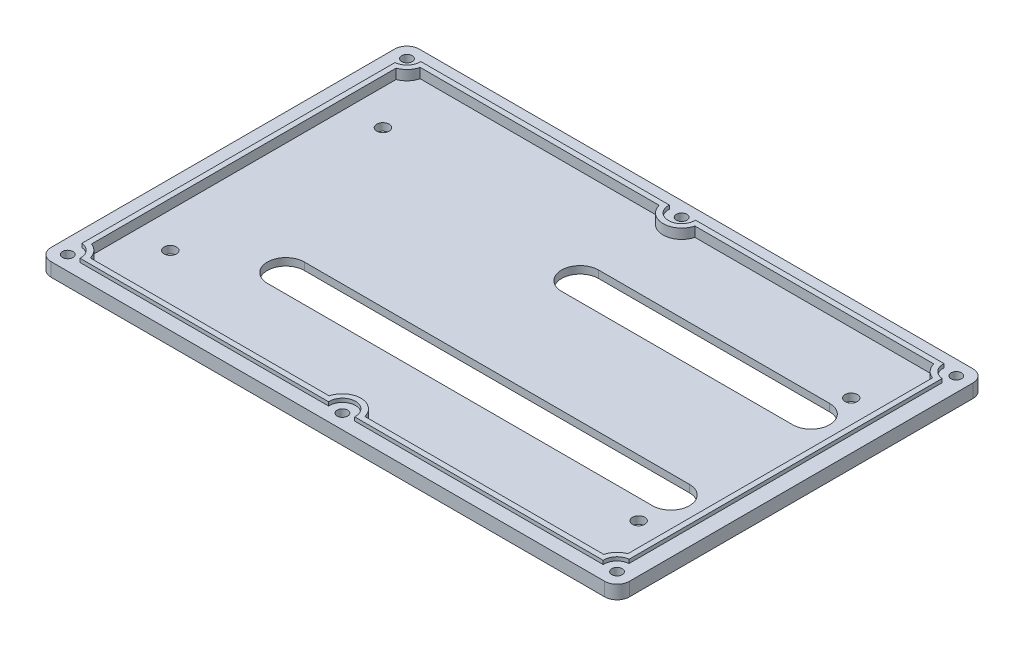
SolidWorks part; units mm, degrees
ref_plane "Front Plane" through (0, 0, 0) normal (0, 0, 1) x (1, 0, 0)
ref_plane "Top Plane" through (0, 0, 0) normal (0, 1, 0) x (1, 0, 0)
ref_plane "Right Plane" through (0, 0, 0) normal (1, 0, 0) x (0, 0, -1)
sketch "Sketch1" plane through (0, 0, 0) normal (0, 1, 0) x (1, 0, 0)
  line L0 (0, 0) -> (0, -54.75) construction
  line L1 (-89.85, 59.75) -> (89.85, 59.75)
  line L2 (-93.85, 55.75) -> (-93.85, -55.75)
  line L3 (-89.85, -59.75) -> (89.85, -59.75)
  line L4 (93.85, 55.75) -> (93.85, -55.75)
  line L5 (-93.85, 59.75) -> (93.85, -59.75) construction
  line L6 (-93.85, -59.75) -> (93.85, 59.75) construction
  line L7 (0, -54.75) -> (88.9, -54.75) construction
  line L8 (88.9, -54.75) -> (88.9, 0.25) construction
  line L9 (88.9, 0.25) -> (71.9, 0.25) construction
  line L10 (71.9, 0.25) -> (53.9, 0.25) construction
  line L11 (0, 0) -> (0, 54.75) construction
  line L12 (0, 54.75) -> (-88.9, 54.75) construction
  line L13 (-88.9, 54.75) -> (-68.9, 54.75) construction
  line L14 (-68.9, 54.75) -> (-68.9, 19.75) construction
  line L15 (-68.9, 19.75) -> (-68.9, -15.25) construction
  arc A0 (-93.85, -55.75) -> (-89.85, -59.75) centre (-89.85, -55.75) ccw
  arc A1 (89.85, -59.75) -> (93.85, -55.75) centre (89.85, -55.75) ccw
  arc A2 (93.85, 55.75) -> (89.85, 59.75) centre (89.85, 55.75) ccw
  arc A3 (-89.85, 59.75) -> (-93.85, 55.75) centre (-89.85, 55.75) ccw
  point P0 (0, 0)
  dimension "D3" = 4
  dimension "D1" = 119.5
  dimension "D2" = 187.7
  dimension "D4" = 17
  dimension "D5" = 35
  dimension "D6" = 55
  dimension "D7" = 88.9
  dimension "D8" = 54.75
  dimension "D9" = 20
  dimension "D10" = 35
  dimension "D11" = 70
extrude "Boss-Extrude1" add sketch "Sketch1" along normal blind 4.4
sketch "Sketch2" plane through (0, 4.4, 0) normal (0, 1, 0) x (1, 0, 0)
  line L0 (89.85, 59.75) -> (-89.85, 59.75) construction
  line L1 (-87.05, 53.55) -> (87.05, 53.55) construction
  line L2 (-87.05, 53.55) -> (-87.05, -53.55) construction
  line L3 (-87.05, -53.55) -> (87.05, -53.55) construction
  line L4 (87.05, 53.55) -> (87.05, -53.55) construction
  line L5 (-87.05, 53.55) -> (87.05, -53.55) construction
  line L6 (-87.05, -53.55) -> (87.05, 53.55) construction
  line L7 (93.85, -55.75) -> (93.85, 55.75) construction
  line L8 (-93.85, 59.75) -> (-89.15, 59.75) construction
  line L9 (-89.15, 59.75) -> (-89.15, 55.05) construction
  line L10 (93.85, 59.75) -> (89.15, 59.75) construction
  line L11 (89.15, 59.75) -> (89.15, 55.05) construction
  line L12 (93.85, -59.75) -> (89.15, -59.75) construction
  line L13 (-89.85, -59.75) -> (89.85, -59.75) construction
  line L14 (89.15, -59.75) -> (89.15, -55.05) construction
  line L15 (-93.85, -59.75) -> (-89.15, -59.75) construction
  line L16 (-89.15, -59.75) -> (-89.15, -55.05) construction
  line L17 (-83.3405, -53.55) -> (-5.8095, -53.55)
  line L18 (87.05, -49.4295) -> (87.05, 49.4295)
  line L19 (5.8095, -53.55) -> (83.3405, -53.55)
  line L20 (-87.05, 49.4295) -> (-87.05, -49.4295)
  line L21 (-89.15, -55.05) -> (89.15, -55.05) construction
  line L22 (-89.15, 55.05) -> (89.15, 55.05) construction
  line L23 (5.8095, 53.55) -> (83.3405, 53.55)
  line L24 (-5.8095, 53.55) -> (-83.3405, 53.55)
  line L25 (89.85, 59.75) -> (-89.85, 59.75) construction
  line L29 (93.85, -55.75) -> (93.85, 55.75) construction
  line L30 (-89.85, -59.75) -> (89.85, -59.75) construction
  line L31 (-93.85, 55.75) -> (-93.85, -55.75) construction
  arc A0 (83.3405, 53.55) -> (87.05, 49.4295) centre (89.15, 55.05) ccw
  arc A1 (-83.3405, 53.55) -> (-87.05, 49.4295) centre (-89.15, 55.05) cw
  arc A2 (-83.3405, -53.55) -> (-87.05, -49.4295) centre (-89.15, -55.05) ccw
  arc A3 (83.3405, -53.55) -> (87.05, -49.4295) centre (89.15, -55.05) cw
  arc A4 (-5.8095, 53.55) -> (5.8095, 53.55) centre (0, 55.05) ccw
  arc A5 (-5.8095, -53.55) -> (5.8095, -53.55) centre (0, -55.05) cw
  point P0 (0, 0)
  point P36 (0, 55.05)
  point P37 (0, -55.05)
  dimension "D4" = 6
  dimension "D1" = 6.2
  dimension "D2" = 6.8
  dimension "D3" = 4.7
extrude "Cut-Extrude1" cut sketch "Sketch2" against normal blind 2
sketch "Sketch3" plane through (0, 4.4, 0) normal (0, 1, 0) x (1, 0, 0)
  line L0 (-87.05, 49.4295) -> (-87.05, -49.4295)
  line L1 (5.8095, -53.55) -> (83.3405, -53.55)
  line L2 (-5.8095, -53.55) -> (-83.3405, -53.55)
  line L3 (87.05, 49.4295) -> (87.05, -49.4295)
  line L4 (5.8095, -53.55) -> (83.3405, -53.55) construction
  line L5 (-88.8, 50.8144) -> (-88.8, -50.8144)
  line L6 (-4.2426, -55.3) -> (-84.9074, -55.3)
  line L7 (4.2426, -55.3) -> (84.9074, -55.3)
  line L8 (88.8, 50.8144) -> (88.8, -50.8144)
  line L9 (-83.3405, 53.55) -> (-5.8095, 53.55)
  line L10 (4.2426, 55.3) -> (84.9074, 55.3)
  line L11 (-84.9074, 55.3) -> (-4.2426, 55.3)
  line L12 (5.8095, 53.55) -> (83.3405, 53.55)
  arc A0 (-87.05, 49.4295) -> (-83.3405, 53.55) centre (-89.15, 55.05) ccw
  arc A1 (-87.05, 49.4295) -> (-83.3405, 53.55) centre (-89.15, 55.05) ccw construction
  arc A2 (87.05, 49.4295) -> (83.3405, 53.55) centre (89.15, 55.05) cw
  arc A3 (83.3405, 53.55) -> (87.05, 49.4295) centre (89.15, 55.05) ccw construction
  arc A4 (-83.3405, -53.55) -> (-87.05, -49.4295) centre (-89.15, -55.05) ccw
  arc A5 (-83.3405, -53.55) -> (-87.05, -49.4295) centre (-89.15, -55.05) ccw construction
  arc A6 (83.3405, -53.55) -> (87.05, -49.4295) centre (89.15, -55.05) cw
  arc A7 (-84.9074, -55.3) -> (-88.8, -50.8144) centre (-89.15, -55.05) ccw
  arc A8 (87.05, -49.4295) -> (83.3405, -53.55) centre (89.15, -55.05) ccw construction
  arc A9 (-4.2426, -55.3) -> (4.2426, -55.3) centre (0, -55.05) cw
  arc A10 (84.9074, -55.3) -> (88.8, -50.8144) centre (89.15, -55.05) cw
  arc A11 (88.8, 50.8144) -> (84.9074, 55.3) centre (89.15, 55.05) cw
  arc A12 (-4.2426, 55.3) -> (4.2426, 55.3) centre (0, 55.05) ccw
  arc A13 (-5.8095, 53.55) -> (5.8095, 53.55) centre (0, 55.05) ccw
  arc A14 (-5.8095, 53.55) -> (5.8095, 53.55) centre (0, 55.05) ccw construction
  arc A15 (-5.8095, -53.55) -> (5.8095, -53.55) centre (0, -55.05) cw
  arc A16 (5.8095, -53.55) -> (-5.8095, -53.55) centre (0, -55.05) ccw construction
  arc A17 (-88.8, 50.8144) -> (-84.9074, 55.3) centre (-89.15, 55.05) ccw
  dimension "D1" = 1.75
extrude "Boss-Extrude3" add sketch "Sketch3" along normal blind 1.2
hole_wizard "CSK for M3 SFHCS1" positions "Sketch5" profile "Sketch4" countersink size "M3" standard "ANSI Metric" end condition through all
sketch "Sketch5" plane through (-54.9521, 0, 58.5759) normal (0, 1, 0) x (1, 0, 0)
  point P0 (-34.1979, 113.6259)
  point P3 (-34.1979, 3.5259)
  point P6 (144.1021, 3.5259)
  point P9 (144.1021, 113.6259)
  point P13 (54.9521, 3.5259)
  point P16 (54.9521, 113.6259)
sketch "Sketch4" plane through (-89.15, 0, -55.05) normal (1, 0, 0) x (0, 0, -1)
  line L0 (0, 0) -> (0, 5.6)
  line L1 (0, 5.6) -> (1.7, 5.6)
  line L2 (1.7, 5.6) -> (1.7, 1.66)
  line L3 (1.7, 1.66) -> (3.36, 0)
  line L5 (3.36, 0) -> (0, 0)
  line L6 (-1.7, 1.66) -> (-3.36, 0) construction
  line L11 (0, -6.35) -> (0, 107.95) construction
  dimension "Thru Hole Dia." = 3.4
  dimension "Thru Hole Depth" = 5.6
  dimension "Near C'Sink Dia." = 6.72
  dimension "Near C'Sink Angle" = 90
hole_wizard "CSK for M3 SFHCS2" positions "Sketch7" profile "Sketch6" countersink size "M3" standard "ANSI Metric"
sketch "Sketch7" plane through (0, 0, 0) normal (0, -1, 0) x (-1, 0, 0)
  point P0 (-71.9, 0.25)
  point P3 (-53.9, 0.25)
  point P7 (68.9, 19.75)
  point P10 (68.9, -15.25)
sketch "Sketch6" plane through (71.9, 0, -0.25) normal (1, 0, 0) x (0, 0, -1)
  line L0 (0, 0) -> (0, 5.6)
  line L1 (0, 5.6) -> (1.7, 5.6)
  line L2 (1.7, 5.6) -> (1.7, 1.66)
  line L3 (1.7, 1.66) -> (3.36, 0)
  line L5 (3.36, 0) -> (0, 0)
  line L6 (-1.7, 1.66) -> (-3.36, 0) construction
  line L11 (0, -6.35) -> (0, 107.95) construction
  dimension "Thru Hole Dia." = 3.4
  dimension "Thru Hole Depth" = 5.6
  dimension "Near C'Sink Dia." = 6.72
  dimension "Near C'Sink Angle" = 90
sketch "Sketch8" plane through (0, 0, 0) normal (0, -1, 0) x (1, 0, 0)
  line L1 (-0.65, -16.75) -> (74.35, -16.75)
  line L2 (-0.65, -16.75) -> (-0.65, -28.75) construction
  line L3 (-0.65, -28.75) -> (74.35, -28.75)
  line L4 (74.35, -16.75) -> (74.35, -28.75) construction
  line L5 (-50.65, 28.75) -> (74.35, 28.75)
  line L6 (-50.65, 28.75) -> (-50.65, 16.75) construction
  line L7 (-50.65, 16.75) -> (74.35, 16.75)
  line L8 (74.35, 28.75) -> (74.35, 16.75) construction
  line L9 (-75.65, 35.25) -> (76.35, 35.25) construction
  line L10 (-75.65, 35.25) -> (-75.65, -33.75) construction
  line L11 (-75.65, -33.75) -> (76.35, -33.75) construction
  line L12 (76.35, 35.25) -> (76.35, -33.75) construction
  line L13 (89.85, -59.75) -> (-89.85, -59.75) construction
  line L14 (93.85, 55.75) -> (93.85, -55.75) construction
  arc A0 (-0.65, -28.75) -> (-0.65, -16.75) centre (-0.65, -22.75) cw
  arc A1 (-50.65, 16.75) -> (-50.65, 28.75) centre (-50.65, 22.75) cw
  arc A2 (74.35, 28.75) -> (74.35, 16.75) centre (74.35, 22.75) cw
  arc A3 (74.35, -16.75) -> (74.35, -28.75) centre (74.35, -22.75) cw
  point P16 (74.35, -22.75)
  point P17 (74.35, 22.75)
  dimension "D2" = 26
  dimension "D3" = 69
  dimension "D4" = 12
  dimension "D5" = 37
  dimension "D6" = 82.5
  dimension "D7" = 12
  dimension "D8" = 75
  dimension "D9" = 125
  dimension "D10" = 17.5
  dimension "D11" = 19.5
  dimension "D12" = 152
extrude "Cut-Extrude2" cut sketch "Sketch8" against normal through all
hole_wizard "Ø4.0 (4) Diameter Hole1" positions "Sketch9" profile "Sketch10" hole size "Ø4.0" standard "ANSI Metric" end condition through all
sketch "Sketch9" plane through (0, 0, 0) normal (0, -1, 0) x (-1, 0, 0)
  point P0 (75.65, -35.25)
  point P3 (75.65, 33.75)
  point P6 (-76.35, 33.75)
  point P9 (-76.35, -35.25)
sketch "Sketch10" plane through (-75.65, 0, 35.25) normal (1, 0, 0) x (0, 0, -1)
  line L0 (0, 0) -> (0, 5.6)
  line L1 (0, 5.6) -> (2, 5.6)
  line L2 (2, 5.6) -> (2, 0)
  line L5 (2, 0) -> (0, 0)
  line L11 (0, -6.35) -> (0, 107.95) construction
  dimension "Thru Hole Dia." = 4
  dimension "Thru Hole Depth" = 5.6
